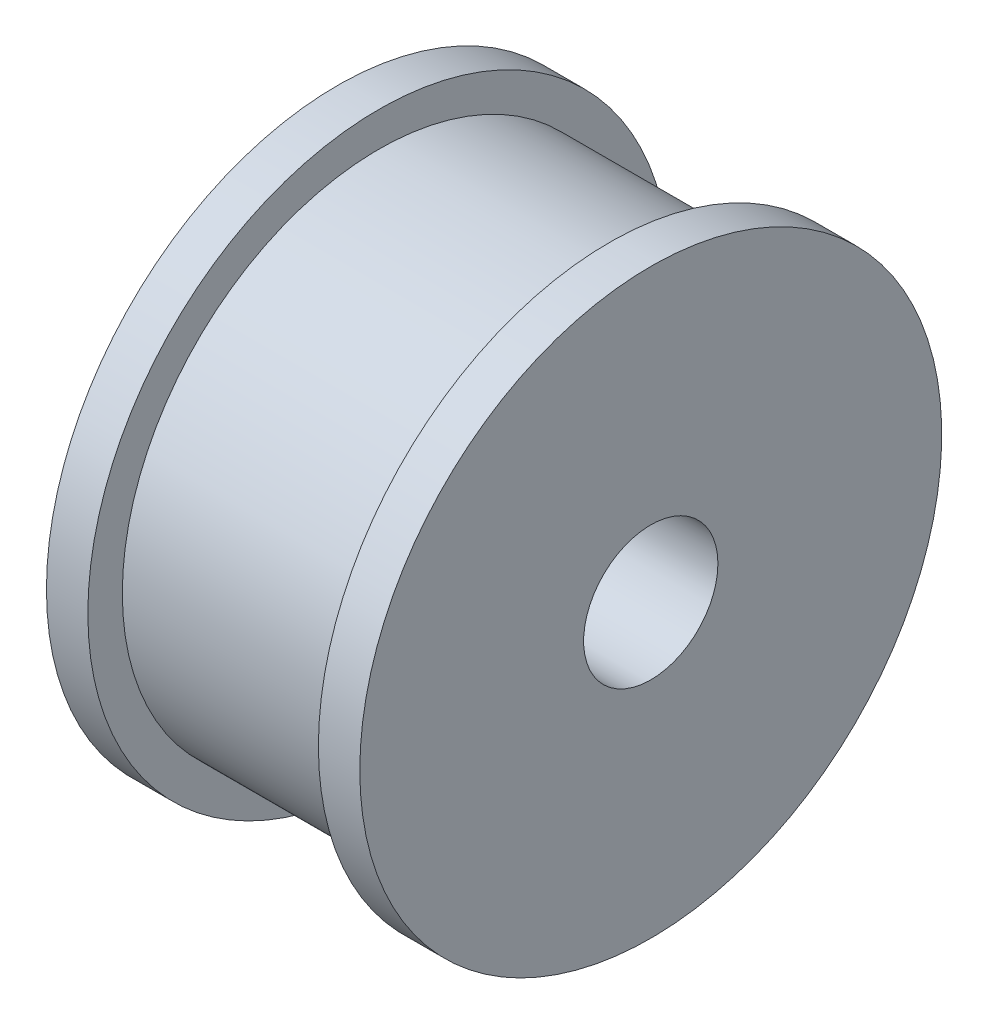
SolidWorks part; units mm, degrees
ref_plane "Front Plane" through (0, 0, 0) normal (0, 0, 1) x (1, 0, 0)
ref_plane "Top Plane" through (0, 0, 0) normal (0, 1, 0) x (1, 0, 0)
ref_plane "Right Plane" through (0, 0, 0) normal (1, 0, 0) x (0, 0, -1)
sketch "Sketch1" plane through (0, 0, 0) normal (0, 1, 0) x (1, 0, 0)
  line L0 (0, -11.46) -> (-5.15, -11.46)
  line L1 (-5.15, -13) -> (-7, -13)
  line L2 (-7, -13) -> (-7, 0)
  line L3 (7, 0) -> (7, -13)
  line L4 (7, -13) -> (5.15, -13)
  line L5 (5.15, -13) -> (5.15, -11.46)
  line L6 (5.15, -11.46) -> (0, -11.46)
  line L7 (-5.15, -11.46) -> (-5.15, -13)
  line L8 (-7, 0) -> (7, 0) construction
  line L9 (7, 0) -> (-7, 0)
  dimension "D1" = 13
  dimension "D2" = 1.85
  dimension "D3" = 7
  dimension "D4" = 11.46
  dimension "D5" = 7
  dimension "D6" = 1.85
revolve "Revolve1" add sketch "Sketch1" angle 360 about L8
hole_wizard "Ø6.0 (6) Diameter Hole2" positions "Sketch8" profile "Sketch7" hole size "Ø6.0" standard "ANSI Metric"
sketch "Sketch8" plane through (7, 0, 0) normal (1, 0, 0) x (0, 0, -1)
  point P0 (0, 0)
sketch "Sketch7" plane through (7, 0, 0) normal (0, 1, 0) x (0, 0, -1)
  line L0 (0, 0) -> (0, 25.8026)
  line L1 (0, 25.8026) -> (3, 24)
  line L2 (3, 24) -> (3, 0)
  line L5 (3, 0) -> (0, 0)
  line L10 (0, 25.8026) -> (-3, 24) construction
  line L11 (0, -6.35) -> (0, 107.95) construction
  dimension "Hole Dia." = 6
  dimension "Hole Depth" = 24
  dimension "Drill Angle" = 118
